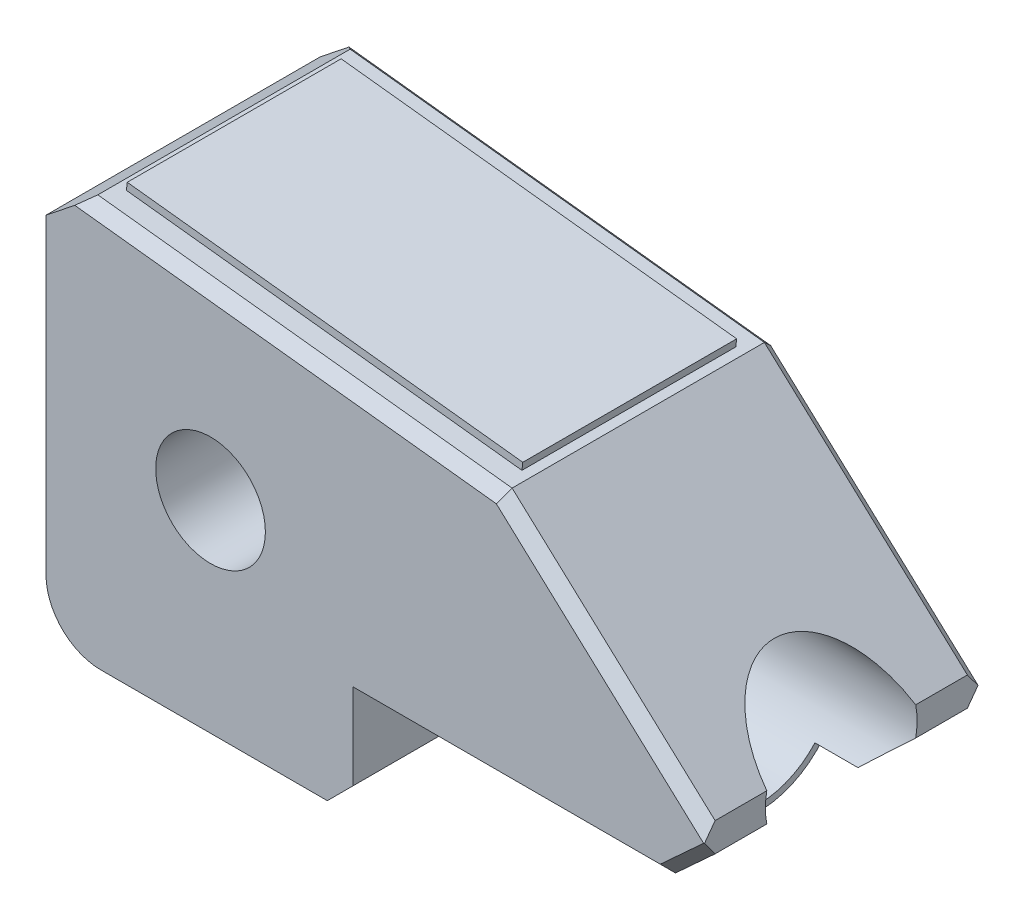
SolidWorks part; units mm, degrees
ref_plane "Front Plane" through (0, 0, 0) normal (0, 0, 1) x (1, 0, 0)
ref_plane "Top Plane" through (0, 0, 0) normal (0, 1, 0) x (1, 0, 0)
ref_plane "Right Plane" through (0, 0, 0) normal (1, 0, 0) x (0, 0, -1)
sketch "Sketch2" plane through (0, 0, 0) normal (0, 0, 1) x (1, 0, 0)
  line L0 (40.1937, 38.9807) -> (-42.7914, 48.3636)
  line L1 (-42.7914, 48.3636) -> (-42.7914, -25.2273)
  line L2 (-42.7914, -25.2273) -> (8.4998, -25.2273)
  line L5 (69.9903, -6.9018) -> (77.2086, -0.2714)
  line L6 (77.2086, -0.2714) -> (77.2086, 4.9807)
  line L7 (77.2086, 4.9807) -> (40.1937, 38.9807)
  line L8 (69.9903, -6.9018) -> (13.1404, -6.9018)
  line L9 (13.1404, -6.9018) -> (13.1404, -20.5866)
  line L10 (13.1404, -20.5866) -> (8.4998, -25.2273)
  circle A0 centre (-12.7914, 11.5681) radius 10
extrude "Boss-Extrude1" add sketch "Sketch2" along normal blind 50
sketch "Sketch3" plane through (77.2086, 0, 0) normal (1, 0, 0) x (0, 0, -1)
  line L0 (-25, -0.2714) -> (-25, 4.9807)
  line L1 (-50, -0.2714) -> (0, -0.2714) construction
  line L2 (-50, 4.9807) -> (0, 4.9807) construction
  circle A0 centre (-25, 2.3546) radius 13.8256
  line M2 (0, 4.9807) -> (-50, 4.9807)
  line M4 (-50, -0.2714) -> (0, -0.2714)
extrude "Cut-Extrude1" cut sketch "Sketch3" along direction (-1, 0, 0) on the side against the normal up to surface (64.0682 mm away) contours A0 M2 | A0 L0 M4 M2 | A0 M4 | A0 L0 M2 M4
sketch "Sketch4" plane through (13.1404, 0, 0) normal (1, 0, 0) x (0, 0, -1)
  line L0 (-13.1967, -6.9018) -> (-14.7303, -6.9018)
  line L1 (-14.7303, -6.9018) -> (0, -6.9018) construction
  line L2 (-35.2697, -6.9018) -> (-36.8033, -6.9018)
  line L3 (-50, -6.9018) -> (-35.2697, -6.9018) construction
  arc A0 (-36.8033, -6.9018) -> (-13.1967, -6.9018) centre (-25, 2.3546) ccw
  arc A1 (-35.2697, -6.9018) -> (-14.7303, -6.9018) centre (-25, 2.3546) ccw
extrude "Boss-Extrude2" add sketch "Sketch4" along normal blind 49
fillet "Fillet1" radius 10 1 edges at (-42.7914, -25.2273, 25)
chamfer "Chamfer1" distance 7.5 angle 45 1 edges at (-42.7914, 48.3636, 25)
chamfer "Chamfer2" distance 2 angle 45 4 edges at (58.7011, 21.9807, 50) (2.4274, 43.2508, 50) (58.7011, 21.9807, 0) (2.4274, 43.2508, 0)
chamfer "Chamfer3" distance 2 angle 45 4 edges at (41.5653, -6.9018, 50) (73.5994, -3.5866, 50) (73.5994, -3.5866, 0) (41.5653, -6.9018, 0)
fillet "Fillet2" radius 2 3 edges at (13.1404, -12.6454, 25) (13.1404, -6.9018, 42.4017) (13.1404, -6.9018, 7.5983)
scale "Scale1" scale about centroid uniform scaling yes scale factor 2
scale "Scale2" scale about centroid uniform scaling yes scale factor 1.1
sketch "Sketch5" plane through (9.0345, 79.9037, 0) normal (0.1124, 0.9937, 0) x (0.9937, -0.1124, 0)
  line L0 (-89.3998, -25) -> (77.8308, -25)
  line L1 (-89.3998, 25.6) -> (-89.3998, -75.6) construction
  line L2 (77.8308, -75.6) -> (77.8308, 25.6) construction
  line L4 (-85.6206, -67.8907) -> (74.0516, -67.8907)
  line L5 (-85.6206, -67.8907) -> (-85.6206, 17.8908)
  line L6 (-85.6206, 17.8908) -> (74.0516, 17.8908)
  line L7 (74.0516, -67.8907) -> (74.0516, 17.8908)
  line L8 (-85.6206, -67.8907) -> (74.0516, 17.8908) construction
  line L9 (-85.6206, 17.8908) -> (74.0516, -67.8907) construction
  point P6 (-5.7845, -25)
extrude "Boss-Extrude3" add sketch "Sketch5" along normal blind 3 contours L4 L7 L0 L5 | L0 L7 L6 L5
